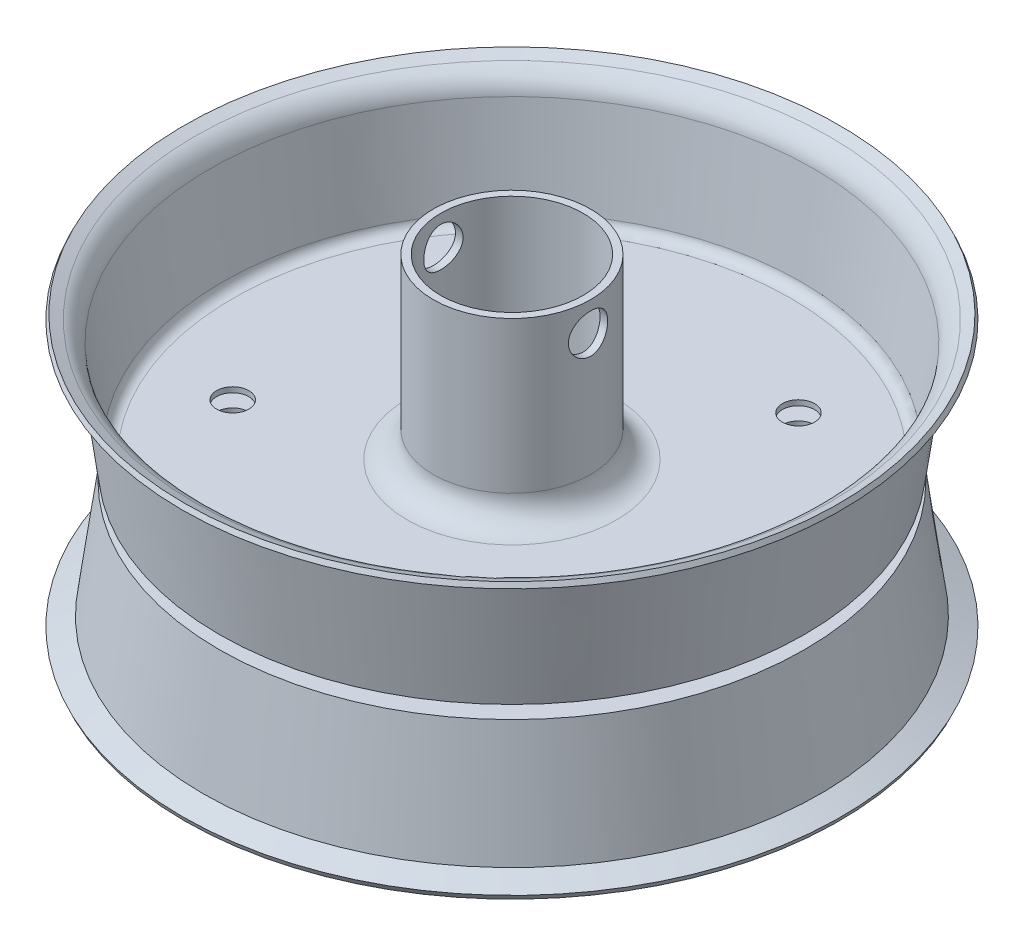
SolidWorks part; units mm, degrees
material "Alloy Steel"
ref_plane "Front Plane" through (0, 0, 0) normal (0, 0, 1) x (1, 0, 0)
ref_plane "Top Plane" through (0, 0, 0) normal (0, 1, 0) x (1, 0, 0)
ref_plane "Right Plane" through (0, 0, 0) normal (1, 0, 0) x (0, 0, -1)
sketch "Sketch1" plane through (0, 0, 0) normal (0, 1, 0) x (1, 0, 0)
  circle A0 centre (0, 0) radius 19.05
  circle A1 centre (0, 0) radius 17.272
  dimension "D1" = 34.544
  dimension "D2" = 38.1
extrude "Boss-Extrude1" add sketch "Sketch1" along normal blind 73.152
ref_plane "Plane1" through (0, 30.099, 0) normal (0, 1, 0) x (1, 0, 0)
sketch "Sketch3" plane through (0, 0, 0) normal (1, 0, 0) x (0, 0, -1)
  line L0 (-19.05, 30.099) -> (-69.85, 30.099)
  line L1 (20.955, 30.099) -> (-20.955, 30.099) construction
  line L2 (-69.85, 30.099) -> (-73.66, 58.039)
  line L3 (-73.66, 58.039) -> (-79.375, 60.579)
  line L4 (-19.05, 28.829) -> (-70.9586, 28.829)
  line L5 (-70.9586, 28.829) -> (-74.8227, 57.166)
  line L6 (-74.8227, 57.166) -> (-79.8908, 59.4185)
  line L7 (-79.375, 60.579) -> (-79.8908, 59.4185)
  line L8 (0, 73.152) -> (0, 28.829) construction
  line L9 (19.05, 73.152) -> (-19.05, 73.152) construction
  line L10 (-19.05, 28.829) -> (-19.05, 30.099)
  line L11 (-19.05, 73.152) -> (-19.05, 0) construction
  line L12 (0, 30.099) -> (-69.85, 30.099) construction
  line L13 (0, 28.829) -> (-70.9586, 28.829) construction
  dimension "D1" = 69.85
  dimension "D2" = 73.66
  dimension "D3" = 79.375
  dimension "D4" = 30.48
  dimension "D5" = 27.94
  dimension "D6" = 1.27
revolve "Revolve1" add sketch "Sketch3" angle 360 about L8
fillet "Fillet1" radius 6.35 1 edges at (0, 30.099, 19.05)
fillet "Fillet2" radius 2.54 1 edges at (0, 30.099, 69.85)
fillet "Fillet3" radius 6.35 1 edges at (0, 58.039, 73.66)
ref_plane "Plane2" through (0, 27.2415, 0) normal (0, -1, 0) x (-1, 0, 0)
sketch "Sketch2" plane through (0, 30.099, 0) normal (0, 1, 0) x (1, 0, 0)
  circle A0 centre (-34.6148, 37.4844) radius 3.9
  circle A1 centre (24.9533, 44.504) radius 3.9
  circle A2 centre (50.0368, -9.9795) radius 3.9
  circle A3 centre (5.9712, -50.6716) radius 3.9
  circle A4 centre (-46.3464, -21.3373) radius 3.9
  point P0 (-34.6148, 37.4844)
  point P14 (0, 0)
  dimension "D2" = 7.8
  dimension "D1" = 51.0222
  dimension "D3" = 5
extrude "Cut-Extrude1" cut sketch "Sketch2" against normal up to next
mirror "Mirror1" about plane through (0, 27.2415, 0) normal (0, -1, 0) of "Cut-Extrude1", "Fillet3", "Fillet2", "Fillet1", "Revolve1"
sketch "Sketch4" plane through (0, 0, 0) normal (1, 0, 0) x (0, 0, -1)
  line L0 (0, 0) -> (0, 84.6072) construction
  circle A0 centre (0, 66.04) radius 4.7625
  circle A1 centre (0, 10.16) radius 4.7625
  dimension "D2" = 9.525
  dimension "D3" = 10.16
  dimension "D1" = 66.04
extrude "Cut-Extrude2" cut sketch "Sketch4" against normal up to next and the other way up to next
